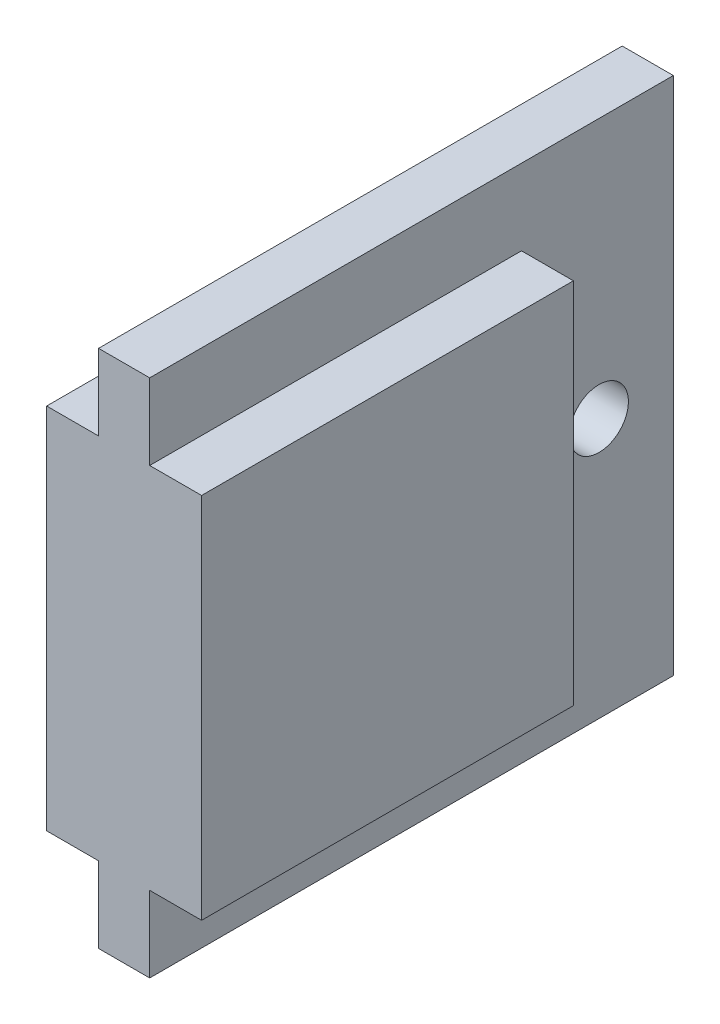
SolidWorks part; units mm, degrees
ref_plane "Front Plane" through (0, 0, 0) normal (1, 0, 0) x (0, 1, 0)
ref_plane "Top Plane" through (0, 0, 0) normal (0, 0, 1) x (0, 1, 0)
ref_plane "Right Plane" through (0, 0, 0) normal (0, 1, 0) x (-1, 0, 0)
sketch "Sketch1" plane through (0, 0, 0) normal (1, 0, 0) x (0, 1, 0)
  line L1 (0, 0) -> (23.75, 0)
  line L2 (0, 0) -> (0, 24)
  line L3 (0, 24) -> (23.75, 24)
  line L4 (23.75, 0) -> (23.75, 24)
  dimension "D1" = 23.75
  dimension "D2" = 24
extrude "Boss-Extrude1" add sketch "Sketch1" against normal blind 10
sketch "Sketch2" plane through (0, 0, 0) normal (0, -1, 0) x (1, 0, 0)
  line L1 (-10, 0) -> (-6.65, 0)
  line L2 (-10, 0) -> (-10, -9.8)
  line L3 (-10, -9.8) -> (-6.65, -9.8)
  line L4 (-6.65, 0) -> (-6.65, -9.8)
  line L5 (0, 0) -> (-3.35, 0)
  line L6 (0, 0) -> (0, -9.8)
  line L7 (0, -9.8) -> (-3.35, -9.8)
  line L8 (-3.35, 0) -> (-3.35, -9.8)
  line L9 (-6.65, -9.8) -> (-3.35, -9.8)
  line L10 (-6.65, -9.8) -> (-6.65, 0)
  line L11 (-6.65, 0) -> (-3.35, 0)
  line L12 (-3.35, -9.8) -> (-3.35, 0)
  line M12 (-10, 0) -> (0, 0)
  dimension "D1" = 9.8
  dimension "D2" = 3.35
  dimension "D3" = 3.35
extrude "Boss-Extrude2" add sketch "Sketch2" against normal through all contours L4 L9 L8 M12
sketch "Sketch3" plane through (0, 0, 0) normal (0, -1, 0) x (1, 0, 0)
  line L0 (-3.35, 20.65) -> (-3.35, 3.35)
  line L1 (0, 24) -> (-10, 24)
  line L2 (0, 24) -> (0, 0)
  line L3 (0, 0) -> (-10, 0)
  line L4 (-10, 24) -> (-10, 0)
  line L5 (-3.35, 3.35) -> (-6.65, 3.35)
  line L6 (-6.65, 20.65) -> (-6.65, 3.35)
  line L7 (-3.35, 20.65) -> (-6.65, 20.65)
  line L9 (-6.65, 20.65) -> (-3.35, 20.65)
  line L10 (-6.65, 20.65) -> (-6.65, 24)
  line L11 (-6.65, 24) -> (-3.35, 24)
  line L12 (-3.35, 20.65) -> (-3.35, 24)
  line L13 (-6.65, 3.35) -> (-3.35, 3.35)
  line L14 (-6.65, 3.35) -> (-6.65, -9.8)
  line L15 (-6.65, -9.8) -> (-3.35, -9.8)
  line L16 (-3.35, 3.35) -> (-3.35, -9.8)
  line M13 (-6.65, 0) -> (-6.65, -9.8)
  line M14 (-6.65, -9.8) -> (-3.35, -9.8)
  line M15 (-3.35, -9.8) -> (-3.35, 0)
  dimension "D1" = 3.35
extrude "Boss-Extrude3" add sketch "Sketch3" along normal blind 4.9 contours L7 L12 L1 L10 | L0 L7 L6 L5 | L16 L5 L14 L3 | L3 M15 M13 M14
sketch "Sketch4" plane through (-6.65, 0, 0) normal (-1, 0, 0) x (0, -1, 0)
  line L0 (0, 0) -> (-23.75, 0) construction
  line L1 (-11.875, 0) -> (-23.75, 0)
  line L2 (-11.875, 0) -> (-11.875, -5)
  line L3 (-11.875, -5) -> (-23.75, -5)
  line L4 (-23.75, 0) -> (-23.75, -5)
  circle A0 centre (-11.875, -5) radius 1.9
  dimension "D2" = 3.8
  dimension "D1" = 5
extrude "Cut-Extrude1" cut sketch "Sketch4" against normal up to next contours A0
sketch "Sketch5" plane through (0, 23.75, 0) normal (0, 1, 0) x (-1, 0, 0)
  line L0 (3.25, 20.75) -> (3.25, 3.25)
  line L1 (0, 24) -> (10, 24)
  line L2 (0, 24) -> (0, 0)
  line L3 (0, 0) -> (10, 0)
  line L4 (10, 24) -> (10, 0)
  line L5 (3.25, 3.25) -> (6.75, 3.25)
  line L6 (6.75, 20.75) -> (6.75, 3.25)
  line L7 (3.25, 20.75) -> (6.75, 20.75)
  line L9 (3.25, 20.75) -> (6.75, 20.75)
  line L10 (3.25, 20.75) -> (3.25, 24)
  line L11 (3.25, 24) -> (6.75, 24)
  line L12 (6.75, 20.75) -> (6.75, 24)
  dimension "D1" = 3.25
extrude "Cut-Extrude2" [suppressed] cut sketch "Sketch5" against normal blind 5 contours L10 L9 L12 L11 | L0 L5 L6 L7
ref_plane "Plane1" through (0, 11.875, 0) normal (0, -1, 0) x (-1, 0, 0)
mirror "Mirror1" about plane through (0, 11.875, 0) normal (0, -1, 0) of "Boss-Extrude3"
equation "\"whitekey_cutout_length\"= 101.5"
equation "\"key_mount_recess_length\"=50"
equation "\"key_mount_recess_height\"=12.5"
equation "\"key_mount_recess_depth\"=1.5"
equation "\"wall_thickness\"=10"
equation "\"guide_brace_height\"=20"
equation "\"guide_brace_thickness\"=2"
equation "\"dowel_recess_depth\"=10"
equation "\"dowel_recess_offset\"=3.25"
equation "\"base_mount_height\"=40"
equation "\"base_rear_length\"=80"
equation "\"base_front_length\"=111.5"
equation "\"screw_hole_wall_offset\"=7.25"
equation "\"screw_hole_edge_inset\"=\"dowel_recess_depth\"/2"
equation "\"screw_hole_diameter\"=3.8"
equation "\"screw_head_hole_diameter\"=6.7"
equation "\"screw_nut_hole_side_len\"=3.5"
equation "\"screw_shaft_diameter\"=3.5"
equation "\"switch_board_width\"=30"
equation "\"switch_board_wall_offset\"=11.5"
equation "\"heatset_insert_hole_diameter\"=4.8"
equation "\"heatset_insert_hole_depth\"=3.8"
equation "\"D1@Boss-Extrude1\"=\"wall_thickness\""
equation "\"D2@Sketch2\"=\"dowel_recess_offset\"+\"dowel_insert_tolerance\""
equation "\"D3@Sketch2\"=\"dowel_recess_offset\"+\"dowel_insert_tolerance\""
equation "\"D1@Boss-Extrude3\"=\"front_rear_panel_recess_depth\"-\"dowel_insert_tolerance\""
equation "\"D1@Sketch3\"=\"dowel_recess_offset\"+\"dowel_insert_tolerance\""
equation "\"D1@Sketch2\"=\"dowel_recess_depth\"-\"dowel_insert_tolerance\"*2"
equation "\"D1@Sketch4\"=\"screw_hole_edge_inset\""
equation "\"D2@Sketch4\"=\"screw_hole_diameter\""
equation "\"D1@Sketch5\"=\"dowel_recess_offset\""
equation "\"D1@Cut-Extrude2\"=\"front_rear_panel_recess_depth\""
equation "\"screw_nut_recess_offset\"=0.35"
equation "\"screw_head_and_nut_recess_depth\"=2.5"
equation "\"front_rear_panel_width\"=23.75"
equation "\"rod_length_adj\"=0.5"
equation "\"rod_insert_length\"=2.8"
equation "\"D1@Sketch1\"=\"front_rear_panel_width\""
equation "\"switch_board_thickness\"=1.6"
equation "\"front_panel_height\"=24"
equation "\"rod_diameter\"=5"
equation "\"rod_head_diameter\"=8"
equation "\"switch_black_key_mount_height\"=8"
equation "\"switch_white_key_mount_height\"=3"
equation "\"D2@Sketch1\"=\"front_panel_height\""
equation "\"dowel_insert_tolerance\"=0.1"
equation "\"front_rear_panel_recess_depth\"=5"
